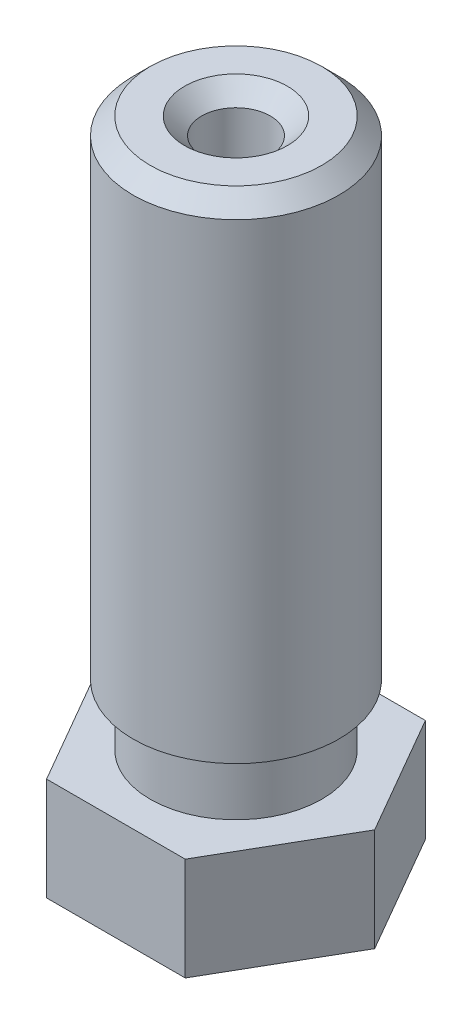
SolidWorks part; units mm, degrees
ref_plane "Front Plane" through (0, 0, 0) normal (0, 0, 1) x (1, 0, 0)
ref_plane "Top Plane" through (0, 0, 0) normal (0, 1, 0) x (1, 0, 0)
ref_plane "Right Plane" through (0, 0, 0) normal (1, 0, 0) x (0, 0, -1)
sketch "Sketch1" plane through (0, 0, 0) normal (0, 1, 0) x (1, 0, 0)
  line L1 (4.0415, 0) -> (2.0207, 3.5)
  line L2 (2.0207, 3.5) -> (-2.0207, 3.5)
  line L3 (-2.0207, 3.5) -> (-4.0415, 0)
  line L4 (-4.0415, 0) -> (-2.0207, -3.5)
  line L5 (-2.0207, -3.5) -> (2.0207, -3.5)
  line L6 (2.0207, -3.5) -> (4.0415, 0)
  circle A0 centre (0, 0) radius 3.5 construction
  dimension "D1" = 7
extrude "Boss-Extrude1" add sketch "Sketch1" along normal blind 21
sketch "Sketch2" plane through (0, 0, 0) normal (0, 0, 1) x (1, 0, 0)
  line L0 (0, 22.1265) -> (0, 0) construction
  line L1 (-1, 1.9856) -> (-1, 21.4459)
  line L2 (-1, 21.4459) -> (0, 21.4459)
  line L3 (-3, 22.8473) -> (-3, 6.7706)
  line L4 (-6.6281, 6.5) -> (8.2576, 6.5) construction
  line L5 (-4.0415, 21) -> (-2.0207, 21) construction
  line L6 (-8.0069, 5) -> (8.7277, 5) construction
  line L7 (-8.3203, 2) -> (10.4513, 2) construction
  line L8 (-0.2, 0) -> (-0.2, 0.6)
  line L9 (-2.0207, 0) -> (2.0207, 0) construction
  line L10 (-0.2, 0.6) -> (-1, 1.9856)
  line L11 (-0.5, 0) -> (-0.5, -1.4731)
  line L12 (-0.5, 0) -> (-1.6547, 2)
  line L13 (-3, 6.7706) -> (-2.5, 6.5)
  line L14 (-2.5, 6.5) -> (-2.5, 5)
  line L15 (-2.5, 5) -> (-6.0122, 5)
  line L16 (-6.0122, 5) -> (-6.0122, 2)
  line L17 (-6.0122, 2) -> (-1.6547, 2)
  line L18 (-0.5, -1.4731) -> (-7.1844, -1.4731)
  line L19 (-7.1844, -1.4731) -> (-7.1844, 22.8473)
  line L20 (-7.1844, 22.8473) -> (-3, 22.8473)
  line L21 (0, 21.4459) -> (0, 0)
  line L22 (0, 0) -> (-0.2, 0)
  dimension "D1" = 2
  dimension "D2" = 6
  dimension "D3" = 14.5
  dimension "D4" = 16
  dimension "D5" = 19
  dimension "D6" = 60
  dimension "D7" = 0.4
  dimension "D8" = 0.6
  dimension "D9" = 1
  dimension "D10" = 5
revolve "Cut-Revolve1" cut sketch "Sketch2" angle 360 about L0
chamfer "Chamfer1" distance 0.5 angle 45 2 edges at (0, 21, 3) (0, 21, 1)
